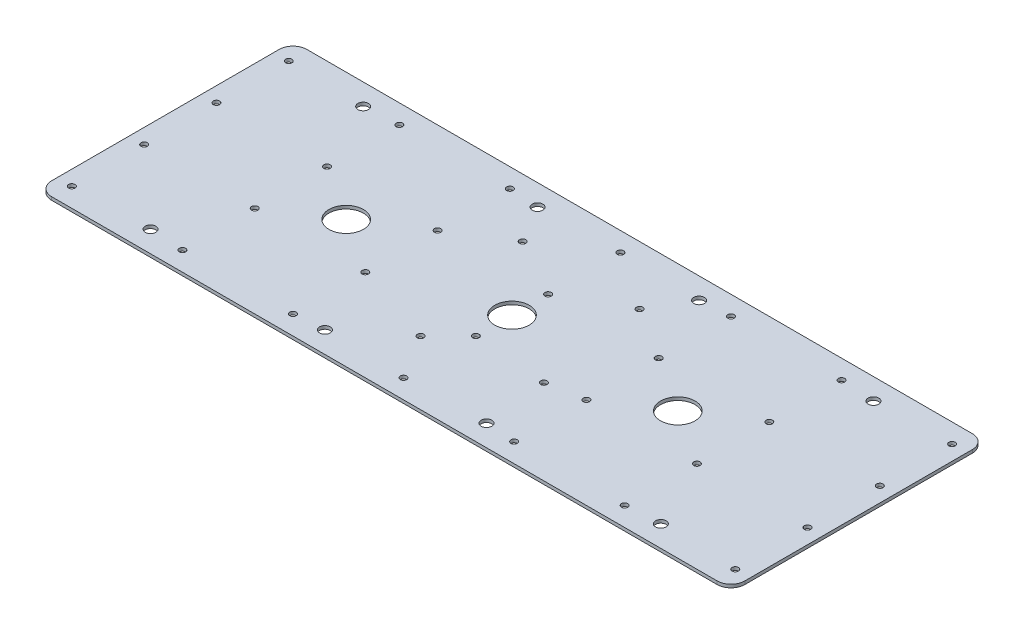
SolidWorks part; units mm, degrees
material "3.3535 (EN-AW 5754)"
ref_plane "Plan de face" through (0, 0, 0) normal (0, 0, 1) x (1, 0, 0)
ref_plane "Plan de dessus" through (0, 0, 0) normal (0, 1, 0) x (1, 0, 0)
ref_plane "Plan de droite" through (0, 0, 0) normal (1, 0, 0) x (0, 0, -1)
sketch "Esquisse1" plane through (0, 0, 0) normal (0, 1, 0) x (1, 0, 0)
  line L1 (0, 60) -> (163, 60)
  line L2 (0, 60) -> (0, -60)
  line L3 (0, -60) -> (163, -60)
  line L4 (163, 60) -> (163, -60)
  dimension "D1" = 120
  dimension "D2" = 163
extrude "Boss.-Extru.1" add sketch "Esquisse1" along normal blind 1.5
fillet "Congé2" radius 6.5 2 edges at (163, 0.75, -60) (163, 0.75, 60)
sketch "Esquisse4" plane through (0, 1.5, 0) normal (0, 1, 0) x (1, 0, 0)
  line L0 (0, 0) -> (163, 0) construction
  line L1 (163, -53.5) -> (163, 53.5) construction
  line L3 (0, -60) -> (156.5, -60) construction
  line L4 (0, 60) -> (0, -60) construction
  circle A0 centre (120, -50) radius 2.5
  circle A1 centre (38, -50) radius 2.5
  circle A2 centre (38, 50) radius 2.5
  circle A3 centre (120, 50) radius 2.5
  dimension "D1" = 10
  dimension "D2" = 5
  dimension "D3" = 120
  dimension "D4" = 82
extrude "Enlèv. mat.-Extru.3" cut sketch "Esquisse4" against normal through all
mirror "Symétrie1" about plane through (0, 1.5, -60) normal (1, 0, 0) of bodies 105 102
sketch "Esquisse6" plane through (0, 1.5, 0) normal (0, 1, 0) x (1, 0, 0)
  line L1 (-25, -20) -> (25, -20)
  line L2 (-25, -20) -> (-25, 20)
  line L3 (-25, 20) -> (25, 20)
  line L4 (25, -20) -> (25, 20)
  line L5 (-25, -20) -> (25, 20) construction
  line L6 (-25, 20) -> (25, -20) construction
  point P0 (0, 0)
  dimension "D1" = 40
  dimension "D2" = 50
extrude "Enlèv. mat.-Extru.4" [suppressed] cut sketch "Esquisse6" against normal through all
fillet "Congé3" [suppressed] radius 5
sketch "Esquisse7" plane through (0, 1.5, 0) normal (0, 1, 0) x (1, 0, 0)
  line L0 (-156.5, -60) -> (156.5, -60) construction
  line L1 (-163, -53.5) -> (-163, 53.5) construction
  circle A0 centre (-156, -51) radius 1.5
  circle A1 centre (-104, -51) radius 1.5
  circle A2 centre (-52, -51) radius 1.5
  circle A3 centre (0, -51) radius 1.5
  circle A4 centre (52, -51) radius 1.5
  circle A5 centre (-104, -17) radius 1.5
  circle A6 centre (-52, -17) radius 1.5
  circle A7 centre (0, -17) radius 1.5
  circle A8 centre (52, -17) radius 1.5
  circle A9 centre (-104, 17) radius 1.5
  circle A10 centre (-52, 17) radius 1.5
  circle A11 centre (0, 17) radius 1.5
  circle A12 centre (52, 17) radius 1.5
  circle A13 centre (-156, -17) radius 1.5
  circle A14 centre (-156, 17) radius 1.5
  circle A15 centre (-156, 51) radius 1.5
  circle A16 centre (-104, 51) radius 1.5
  circle A17 centre (-52, 51) radius 1.5
  circle A18 centre (0, 51) radius 1.5
  circle A19 centre (52, 51) radius 1.5
  circle A20 centre (104, -51) radius 1.5
  circle A21 centre (104, -17) radius 1.5
  circle A22 centre (104, 17) radius 1.5
  circle A23 centre (104, 51) radius 1.5
  circle A24 centre (156, -51) radius 1.5
  circle A25 centre (156, -17) radius 1.5
  circle A26 centre (156, 17) radius 1.5
  circle A27 centre (156, 51) radius 1.5
  circle A28 centre (-120, 50) radius 2.5 construction
  circle A29 centre (-38, 50) radius 2.5 construction
  dimension "D5" = 3
  dimension "D3" = 51
  dimension "D4" = 34
  dimension "D6" = 156
  dimension "D7" = 52
  dimension "D8" = 9
  dimension "D9" = 7
  dimension "D10" = 16
  dimension "D11" = 14
  dimension "D1" = 7
  dimension "D2" = 4
extrude "Enlèv. mat.-Extru.5" cut sketch "Esquisse7" against normal through all
sketch "Esquisse8" plane through (0, 1.5, 0) normal (0, 1, 0) x (1, 0, 0)
  line L0 (-78, 0) -> (78, 0) construction
  circle A0 centre (0, 0) radius 8.1
  circle A1 centre (-78, 0) radius 8.1
  circle A2 centre (78, 0) radius 8.1
  circle A3 centre (-52, 17) radius 1.5 construction
  circle A4 centre (-104, 17) radius 1.5 construction
  dimension "D1" = 26
  dimension "D2" = 26
  dimension "D3" = 16.2
extrude "Enlèv. mat.-Extru.6" cut sketch "Esquisse8" against normal through all
sketch "Esquisse9" plane through (0, 1.5, 0) normal (0, 1, 0) x (1, 0, 0)
  line L1 (0, -0.825) -> (0, 0.825) construction
  circle A1 centre (27.5, 32.5) radius 1.5
  circle A2 centre (-13, -30) radius 1.5
  circle A3 centre (35, -20) radius 1.5
  circle A4 centre (-27.5, 32.5) radius 1.5
  dimension "D1" = 3
  dimension "D2" = 48
  dimension "D3" = 10
  dimension "D4" = 55
  dimension "D5" = 32.5
  dimension "D6" = 30
  dimension "D7" = 13
extrude "Enlèv. mat.-Extru.7" cut sketch "Esquisse9" against normal through all
equation "\"D6@Esquisse7\"=\"D7@Esquisse7\"*(\"D1@Esquisse7\"-1)/2"
equation "\"D3@Esquisse7\"=\"D4@Esquisse7\"*(\"D2@Esquisse7\"-1)/2"
